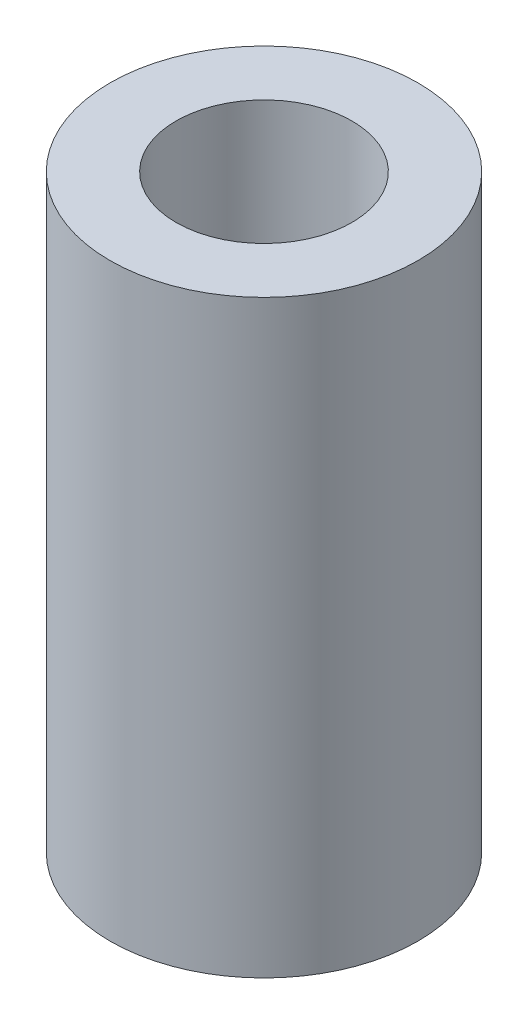
SolidWorks part; units mm, degrees
ref_plane "Front" through (0, 0, 0) normal (0, 0, 1) x (1, 0, 0)
ref_plane "Top" through (0, 0, 0) normal (0, 1, 0) x (1, 0, 0)
ref_plane "Right" through (0, 0, 0) normal (1, 0, 0) x (0, 0, -1)
sketch "Sketch1" plane through (0, 0, 0) normal (0, 1, 0) x (1, 0, 0)
  circle A0 centre (0, 0) radius 1
  circle A1 centre (0, 0) radius 1.75
  dimension "D1" = 3.5
  dimension "D2" = 2
extrude "Boss-Extrude1" add sketch "Sketch1" along normal blind 6.7
